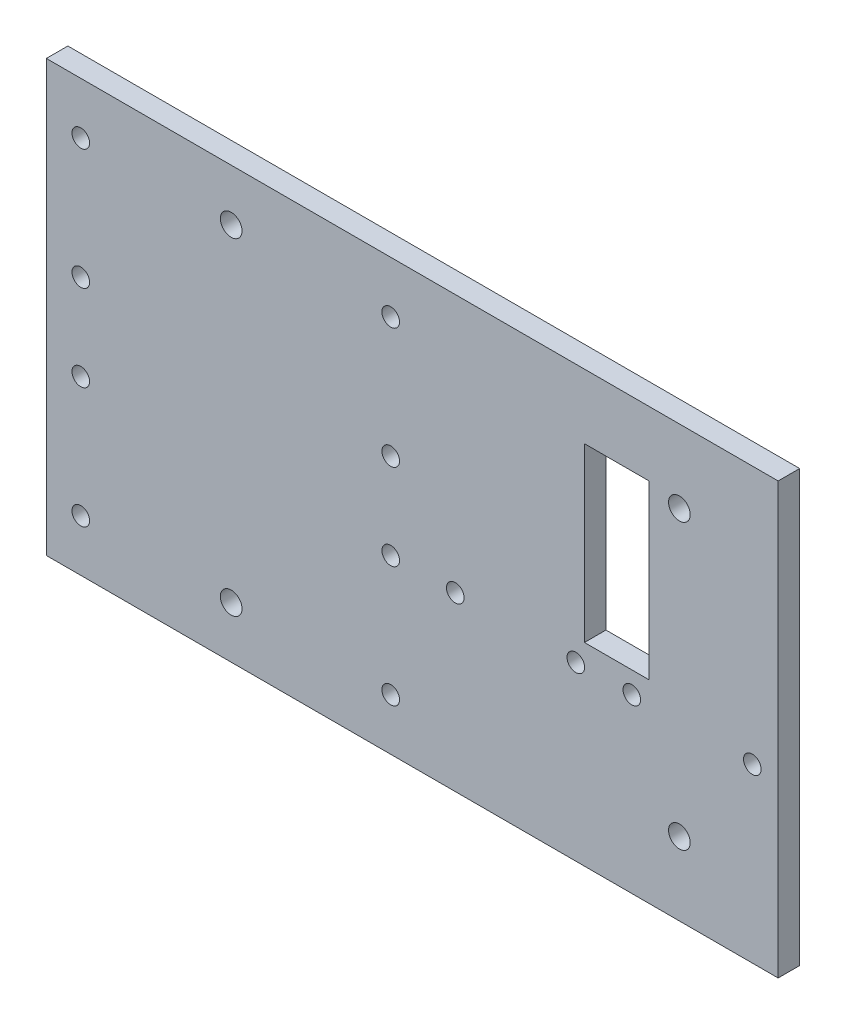
SolidWorks part; units mm, degrees
ref_plane "Front Plane" through (0, 0, 0) normal (0, 0, 1) x (1, 0, 0)
ref_plane "Top Plane" through (0, 0, 0) normal (0, 1, 0) x (1, 0, 0)
ref_plane "Right Plane" through (0, 0, 0) normal (1, 0, 0) x (0, 0, -1)
sketch "Sketch1" plane through (0, 0, 0) normal (0, 0, 1) x (1, 0, 0)
  line L1 (-47.625, 31.75) -> (47.625, 31.75)
  line L2 (-47.625, 31.75) -> (-47.625, -31.75)
  line L3 (-47.625, -31.75) -> (47.625, -31.75)
  line L4 (47.625, 31.75) -> (47.625, -31.75)
  line L5 (-47.625, 31.75) -> (47.625, -31.75) construction
  line L6 (-47.625, -31.75) -> (47.625, 31.75) construction
  point P0 (0, 0)
  dimension "D1" = 95.25
  dimension "D2" = 63.5
extrude "Boss-Extrude1" add sketch "Sketch1" along normal blind 3.175
sketch "Sketch2" plane through (0, 0, 3.175) normal (0, 0, 1) x (1, 0, 0)
  line L1 (-33.0581, 20.955) -> (33.0581, 20.955) construction
  line L2 (-33.0581, 20.955) -> (-33.0581, -20.955) construction
  line L3 (-33.0581, -20.955) -> (33.0581, -20.955) construction
  line L4 (33.0581, 20.955) -> (33.0581, -20.955) construction
  line L5 (-33.0581, 20.955) -> (33.0581, -20.955) construction
  line L6 (-33.0581, -20.955) -> (33.0581, 20.955) construction
  circle A1 centre (33.0581, 20.955) radius 1.6
  circle A2 centre (33.0581, -20.955) radius 1.6
  circle A4 centre (-33.0581, 24.13) radius 1.6
  circle A5 centre (-33.0581, -24.13) radius 1.6
  point P0 (0, 0)
  dimension "D3" = 3.2
  dimension "D4" = 48.26
  dimension "D5" = 24.13
  dimension "D1" = 66.1162
  dimension "D2" = 41.91
extrude "Cut-Extrude1" cut sketch "Sketch2" against normal through all
sketch "Sketch3" plane through (0, 0, 3.175) normal (0, 0, 1) x (1, 0, 0)
  line L1 (19.05, 22.225) -> (28.575, 22.225)
  line L2 (19.05, 22.225) -> (19.05, -3.175)
  line L3 (19.05, -3.175) -> (28.575, -3.175)
  line L4 (28.575, 22.225) -> (28.575, -3.175)
  line L5 (19.05, 22.225) -> (28.575, -3.175) construction
  line L6 (19.05, -3.175) -> (28.575, 22.225) construction
  point P0 (23.8125, 9.525)
  dimension "D1" = 25.4
  dimension "D2" = 9.525
  dimension "D3" = 19.05
  dimension "D4" = 9.525
extrude "Cut-Extrude2" cut sketch "Sketch3" against normal through all and the other way through all
sketch "Sketch5" plane through (0, 0, 3.175) normal (0, 0, 1) x (1, 0, 0)
  line L0 (-47.625, -31.75) -> (47.625, -31.75) construction
  line L1 (-47.625, 31.75) -> (-60.325, 31.75)
  line L2 (-47.625, 31.75) -> (-47.625, -31.75)
  line L3 (-47.625, -31.75) -> (-60.325, -31.75)
  line L4 (-60.325, 31.75) -> (-60.325, -31.75)
  dimension "D1" = 12.7
extrude "Boss-Extrude2" add sketch "Sketch5" against normal blind 3.175
sketch "Sketch6" plane through (0, 0, 3.175) normal (0, 0, 1) x (1, 0, 0)
  line L1 (-55.245, 24.13) -> (-9.525, 24.13)
  line L2 (-55.245, 24.13) -> (-55.245, 6.35)
  line L3 (-55.245, 6.35) -> (-9.525, 6.35)
  line L4 (-9.525, 24.13) -> (-9.525, 6.35)
  line L5 (-55.245, 24.13) -> (-9.525, 6.35) construction
  line L6 (-55.245, 6.35) -> (-9.525, 24.13) construction
  line L7 (-55.245, -6.35) -> (-9.525, -6.35)
  line L8 (-55.245, -6.35) -> (-55.245, -24.13)
  line L9 (-55.245, -24.13) -> (-9.525, -24.13)
  line L10 (-9.525, -6.35) -> (-9.525, -24.13)
  line L11 (-55.245, -6.35) -> (-9.525, -24.13) construction
  line L12 (-55.245, -24.13) -> (-9.525, -6.35) construction
  line L13 (0, -6.35) -> (17.78, -6.35)
  line L14 (0, -6.35) -> (0, -24.13)
  line L15 (0, -24.13) -> (17.78, -24.13)
  line L16 (17.78, -6.35) -> (17.78, -24.13)
  line L17 (0, -6.35) -> (17.78, -24.13) construction
  line L18 (0, -24.13) -> (17.78, -6.35) construction
  line L20 (-6.985, 26.67) -> (-57.785, 26.67)
  line L21 (-6.985, 26.67) -> (-6.985, 3.81)
  line L22 (-6.985, 3.81) -> (-57.785, 3.81)
  line L23 (-57.785, 26.67) -> (-57.785, 3.81)
  line L24 (-6.985, 26.67) -> (-57.785, 3.81) construction
  line L25 (-6.985, 3.81) -> (-57.785, 26.67) construction
  line L26 (-57.785, -3.81) -> (-6.985, -3.81)
  line L27 (-57.785, -3.81) -> (-57.785, -26.67)
  line L28 (-57.785, -26.67) -> (-6.985, -26.67)
  line L29 (-6.985, -3.81) -> (-6.985, -26.67)
  line L30 (-57.785, -3.81) -> (-6.985, -26.67) construction
  line L31 (-57.785, -26.67) -> (-6.985, -3.81) construction
  line L32 (-2.54, -3.81) -> (20.32, -3.81)
  line L33 (-2.54, -3.81) -> (-2.54, -26.67)
  line L34 (-2.54, -26.67) -> (20.32, -26.67)
  line L35 (20.32, -3.81) -> (20.32, -26.67)
  line L36 (-2.54, -3.81) -> (20.32, -26.67) construction
  line L37 (-2.54, -26.67) -> (20.32, -3.81) construction
  line L38 (23.495, -3.81) -> (46.355, -3.81)
  line L39 (23.495, -3.81) -> (23.495, -26.67)
  line L40 (23.495, -26.67) -> (46.355, -26.67)
  line L41 (46.355, -3.81) -> (46.355, -26.67)
  line L42 (23.495, -3.81) -> (46.355, -26.67) construction
  line L43 (23.495, -26.67) -> (46.355, -3.81) construction
  line L44 (26.035, -6.35) -> (43.815, -6.35)
  line L45 (26.035, -6.35) -> (26.035, -24.13)
  line L46 (26.035, -24.13) -> (43.815, -24.13)
  line L47 (43.815, -6.35) -> (43.815, -24.13)
  line L48 (26.035, -6.35) -> (43.815, -24.13) construction
  line L49 (26.035, -24.13) -> (43.815, -6.35) construction
  point P0 (-32.385, 15.24)
  point P5 (-32.385, 15.24)
  point P6 (8.89, -15.24)
  point P7 (-32.385, -15.24)
  point P21 (-32.385, -15.24)
  point P26 (8.89, -15.24)
  point P31 (34.925, -15.24)
  point P38 (34.925, -15.24)
  dimension "D1" = 45.72
  dimension "D2" = 17.78
  dimension "D3" = 17.78
  dimension "D4" = 45.72
  dimension "D5" = 17.78
  dimension "D6" = 17.78
  dimension "D7" = 6.35
  dimension "D8" = 6.35
  dimension "D9" = 9.525
  dimension "D10" = 0
  dimension "D11" = 22.86
  dimension "D12" = 50.8
  dimension "D13" = 50.8
  dimension "D14" = 22.86
  dimension "D15" = 22.86
  dimension "D16" = 22.86
  dimension "D17" = 22.86
  dimension "D18" = 22.86
  dimension "D19" = 3.175
  dimension "D20" = 17.78
sketch "Sketch7" plane through (0, 0, 3.175) normal (0, 0, 1) x (1, 0, 0)
  circle A0 centre (-55.245, 24.13) radius 1.3
  circle A1 centre (-9.525, 24.13) radius 1.3
  circle A2 centre (-9.525, 6.35) radius 1.3
  circle A3 centre (-55.245, 6.35) radius 1.3
  circle A4 centre (-55.245, -6.35) radius 1.3
  circle A5 centre (-9.525, -6.35) radius 1.3
  circle A6 centre (-9.525, -24.13) radius 1.3
  circle A7 centre (-55.245, -24.13) radius 1.3
  dimension "D1" = 2.6
extrude "Cut-Extrude3" cut sketch "Sketch7" against normal through all
sketch "Sketch8" plane through (0, 0, 3.175) normal (0, 0, 1) x (1, 0, 0)
  circle A0 centre (0, -6.35) radius 1.3
  circle A4 centre (43.815, -6.35) radius 1.3
  circle A6 centre (17.78, -6.35) radius 1.3
  circle A7 centre (26.035, -6.35) radius 1.3
  dimension "D1" = 2.6
extrude "Cut-Extrude4" cut sketch "Sketch8" against normal blind 3.175
